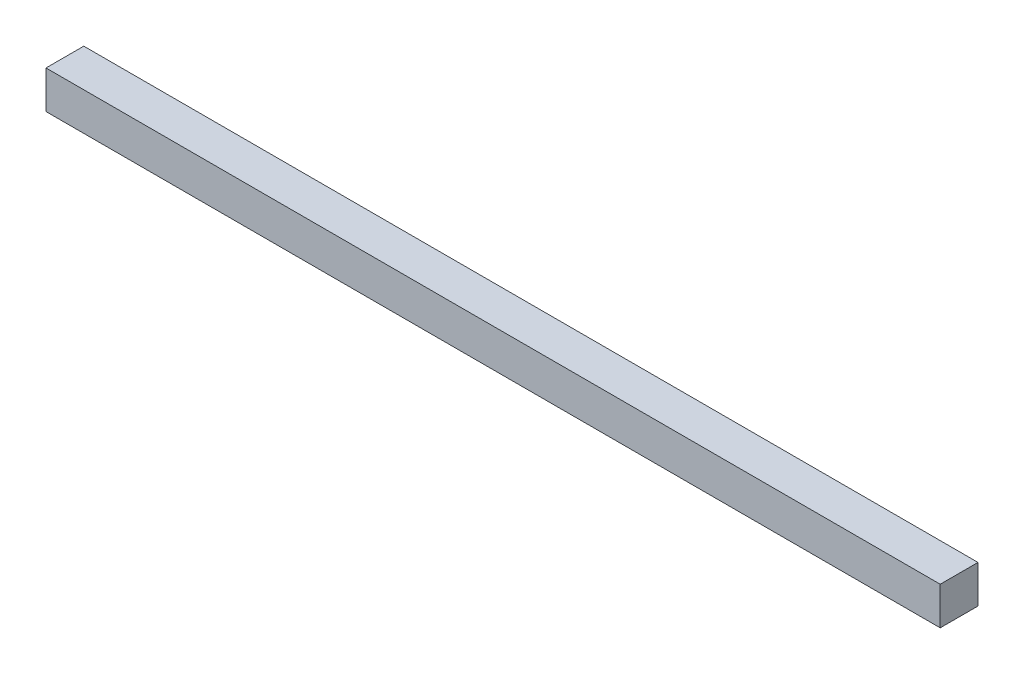
SolidWorks part; units mm, degrees
ref_plane "Front Plane" through (0, 0, 0) normal (0, 0, 1) x (1, 0, 0)
ref_plane "Top Plane" through (0, 0, 0) normal (0, 1, 0) x (1, 0, 0)
ref_plane "Right Plane" through (0, 0, 0) normal (1, 0, 0) x (0, 0, -1)
sketch "Sketch1" plane through (0, 0, 0) normal (0, 0, 1) x (1, 0, 0)
  line L1 (0, 0) -> (142, 0)
  line L2 (0, 0) -> (0, 6)
  line L3 (0, 6) -> (142, 6)
  line L4 (142, 0) -> (142, 6)
  dimension "D1" = 142
  dimension "D2" = 6
extrude "Profile" add sketch "Sketch1" along normal blind 6
equation "\"Profile_Depth\"= 6mm"
equation "\"D1@Profile\" = \"Profile_Depth\""
equation "\"Profile_Sketch_1\"= 142mm"
equation "\"D1@Sketch1\" = \"Profile_Sketch_1\""
equation "\"Profile_Sketch_2\"= 6mm"
equation "\"D2@Sketch1\" = \"Profile_Sketch_2\""
equation "\"EnvelopeWidth\"= 142mm"
equation "\"EnvelopeHeight\"= 6mm"
